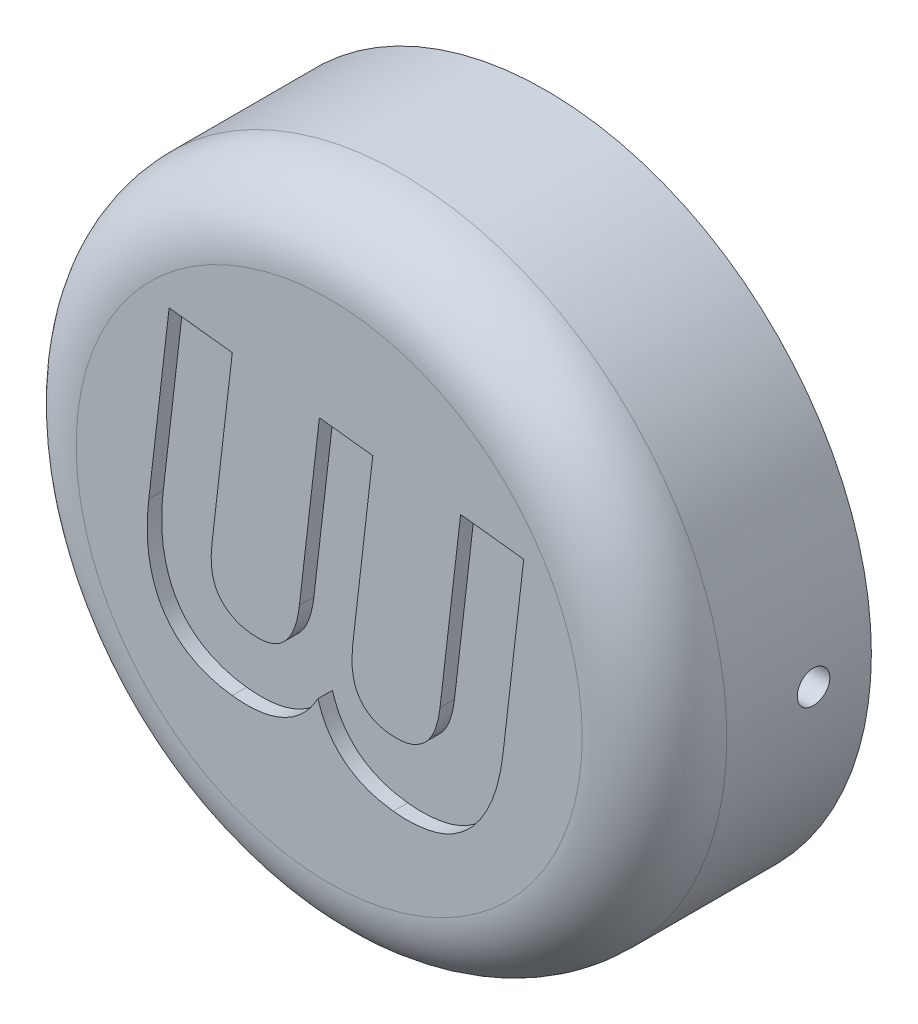
SolidWorks part; units mm, degrees
ref_plane "Plan de face" through (0, 0, 0) normal (0, 0, 1) x (1, 0, 0)
ref_plane "Plan de dessus" through (0, 0, 0) normal (0, 1, 0) x (1, 0, 0)
ref_plane "Plan de droite" through (0, 0, 0) normal (1, 0, 0) x (0, 0, -1)
sketch "Esquisse1" plane through (0, 0, 0) normal (0, 0, 1) x (1, 0, 0)
  circle A0 centre (0, 0) radius 45
  dimension "D1" = 90
extrude "Boss.-Extru.1" add sketch "Esquisse1" along normal blind 30
fillet "Congé1" radius 10 1 edges at (45, 0, 30)
sketch "Esquisse3" plane through (0, 0, 0) normal (0, 0, -1) x (-1, 0, 0)
  circle A0 centre (0, 0) radius 40
  circle A1 centre (0, 0) radius 3.15
  circle A2 centre (0, 0) radius 7
  dimension "D1" = 80
  dimension "D2" = 6.3
  dimension "D3" = 14
extrude "Enlèv. mat.-Extru.1" cut sketch "Esquisse3" against normal blind 15 contours A0 A2 | A1
fillet "Congé2" radius 10 1 edges at (-40, 0, 15)
sketch "Esquisse4" plane through (0, 0, 30) normal (0, 0, 1) x (1, 0, 0)
  text T0 "E" font "Nasalization Rg" height in points 192
extrude "Enlèv. mat.-Extru.2" cut sketch "Esquisse4" against normal blind 2
sketch "Esquisse12" plane through (0, 0, 0) normal (0, 0, -1) x (-1, 0, 0)
  line L1 (0, -7) -> (-14, -7)
  line L2 (0, -7) -> (0, 7)
  line L3 (0, 7) -> (-14, 7)
  line L4 (-14, -7) -> (-14, 7)
  circle A0 centre (0, 0) radius 7 construction
  circle A1 centre (0, 0) radius 7 construction
  circle A2 centre (0, 0) radius 3.15
  circle M1 centre (0, 0) radius 3.15
  circle M2 centre (0, 0) radius 7
  dimension "D1" = 14
  dimension "D2" = 14
  dimension "D3" = 7
extrude "Boss.-Extru.3" add sketch "Esquisse12" against normal blind 22 contours L2 M2 M1 | L4 L1 L3 M2
sketch "Esquisse13" plane through (14, 0, 0) normal (1, 0, 0) x (0, 0, -1)
  line L0 (-15, 7) -> (0, 7) construction
  line L1 (-10.1651, 3.75) -> (-12.3301, 0)
  line L2 (-12.3301, 0) -> (-10.1651, -3.75)
  line L3 (-10.1651, -3.75) -> (-5.8349, -3.75)
  line L4 (-5.8349, -3.75) -> (-3.6699, 0)
  line L5 (-3.6699, 0) -> (-5.8349, 3.75)
  line L6 (-5.8349, 3.75) -> (-10.1651, 3.75)
  line L7 (0, -7) -> (0, 7) construction
  circle A0 centre (-8, 0) radius 3.75 construction
  dimension "D1" = 7.5
  dimension "D2" = 0
  dimension "D3" = 8
  dimension "D4" = 7
extrude "Enlèv. mat.-Extru.3" cut sketch "Esquisse13" against normal blind 8
sketch "Esquisse14" plane through (0, 0, 0) normal (0, 0, -1) x (-1, 0, 0)
  line L0 (-14, -7) -> (-14, 7) construction
  line L1 (-14, 3.75) -> (-6, 3.75)
  line L2 (-14, 3.75) -> (-14, -3.75)
  line L3 (-14, -3.75) -> (-6, -3.75)
  line L4 (-6, 3.75) -> (-6, -3.75)
  line L5 (0, 7) -> (-14, 7) construction
  point P6 (-6, 0)
  dimension "D1" = 7.5
  dimension "D2" = 7
  dimension "D3" = 8
extrude "Enlèv. mat.-Extru.4" cut sketch "Esquisse14" against normal blind 8
sketch "Esquisse15" plane through (0, 0, 15) normal (0, 0, -1) x (-1, 0, 0)
  line L1 (-14, 7) -> (-15.5, 7)
  line L2 (-14, 7) -> (-14, -7)
  line L3 (-14, -7) -> (-15.5, -7)
  line L4 (-15.5, 7) -> (-15.5, -7)
  line L5 (-14, 7) -> (-11.5, 7)
  line L6 (-14, 7) -> (-14, -7)
  line L7 (-14, -7) -> (-11.5, -7)
  line L8 (-11.5, 7) -> (-11.5, -7)
  line M8 (0, -7) -> (-14, -7)
  line M9 (-14, -7) -> (-14, 7)
  line M10 (-14, 7) -> (0, 7)
  dimension "D1" = 14
  dimension "D2" = 4
  dimension "D3" = 5.5
extrude "Boss.-Extru.4" add sketch "Esquisse15" along normal blind 15 contours L1 L4 L3 M9 | L8 M10 M9 M8
sketch "Esquisse16" plane through (15.5, 0, 0) normal (1, 0, 0) x (0, 0, -1)
  line L0 (0, 7) -> (-15, 7) construction
  line L2 (0, 7) -> (0, -7) construction
  circle A0 centre (-8, 0) radius 2.25
  point P6 (0, 0.8971)
  dimension "D3" = 4.5
  dimension "D1" = 7
  dimension "D2" = 8
extrude "Enlèv. mat.-Extru.5" cut sketch "Esquisse16" against normal blind 15 and the other way blind 31
fillet "Congé3" radius 5 4 edges at (7.75, -7, 15) (15.5, 0, 15) (-7, 0, 15) (7.75, 7, 15)
sketch "Esquisse17" plane through (15.5, 0, 0) normal (1, 0, 0) x (0, 0, -1)
  circle A0 centre (-8.3177, 0) radius 7
extrude "Enlèv. mat.-Extru.6" cut sketch "Esquisse17" along normal blind 8
